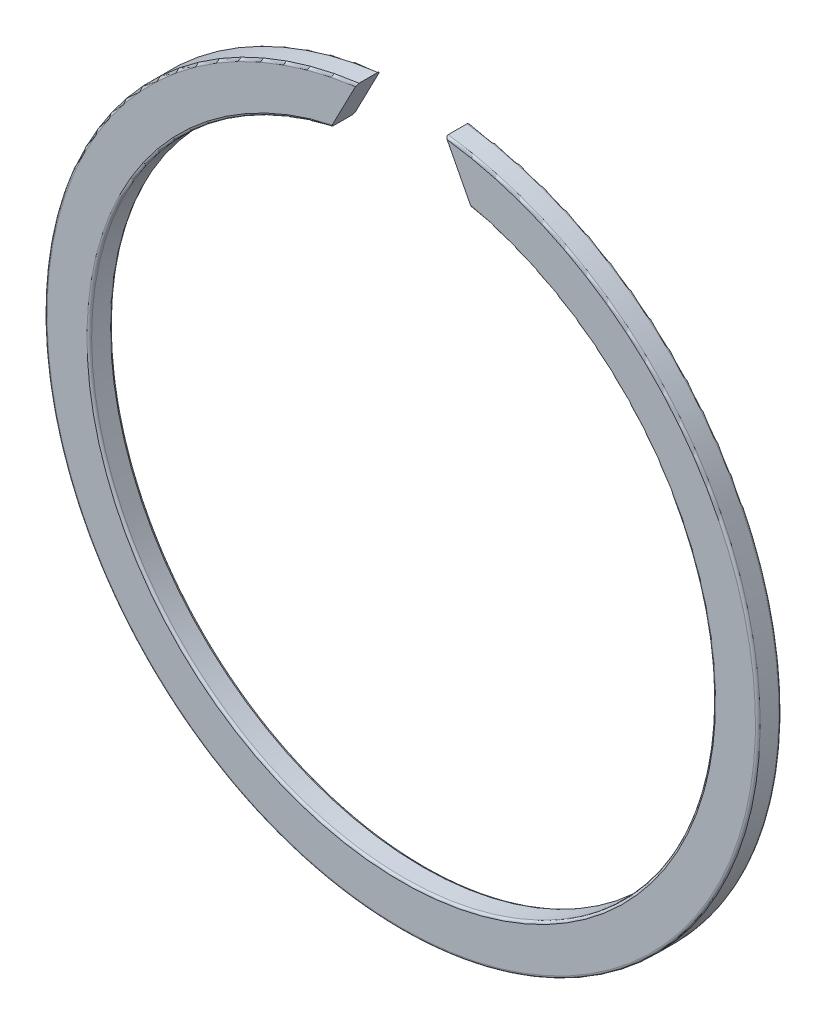
SolidWorks part; units mm, degrees
ref_plane "Plano frontal" through (0, 0, 0) normal (0, 0, 1) x (1, 0, 0)
ref_plane "Plano superior" through (0, 0, 0) normal (0, 1, 0) x (1, 0, 0)
ref_plane "Plano direito" through (0, 0, 0) normal (1, 0, 0) x (0, 0, -1)
sketch "Esboço1" plane through (0, 0, 0) normal (0, 0, 1) x (1, 0, 0)
  line L0 (-4.75, 37.702) -> (-7.5, 32.3931)
  line L5 (4.75, 37.702) -> (7.5, 32.3931)
  arc A0 (-4.75, 37.702) -> (4.75, 37.702) centre (0, 0) ccw
  arc A2 (-7.5, 32.3931) -> (7.5, 32.3931) centre (0, 0) ccw
extrude "Ressalto-extrusão1" add sketch "Esboço1" along normal blind 2.5
fillet "Filete1" radius 0.25 4 edges at (0, -33.25, 0) (0, -33.25, 2.5) (0, -38, 2.5) (0, -38, 0)
